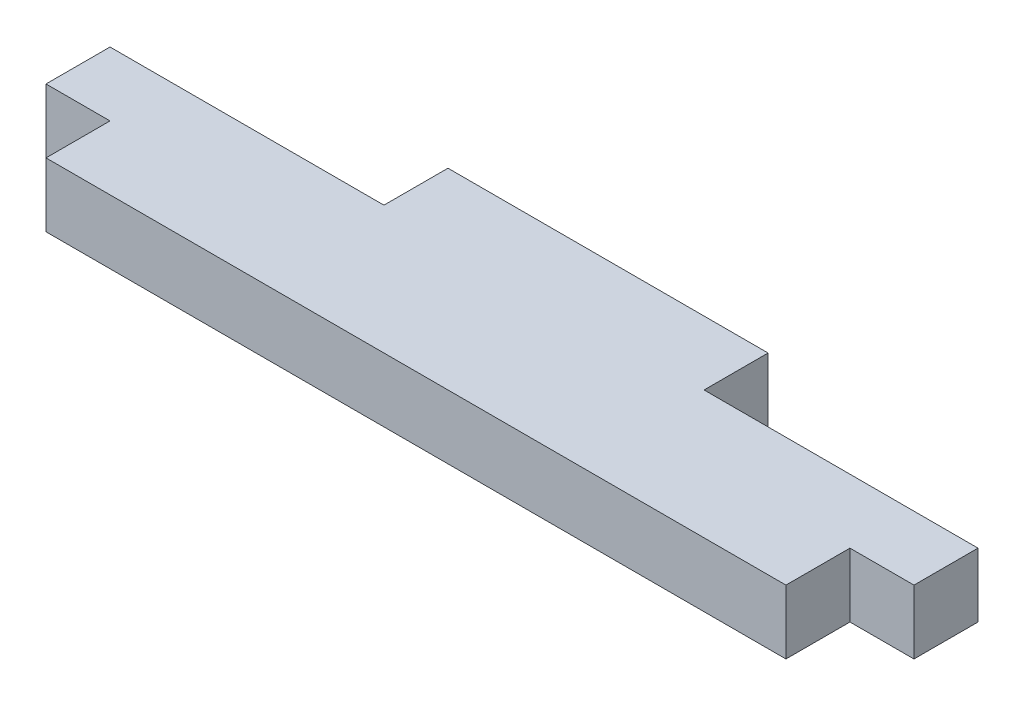
SolidWorks part; units mm, degrees
ref_plane "Front Plane" through (0, 0, 0) normal (0, 0, 1) x (1, 0, 0)
ref_plane "Top Plane" through (0, 0, 0) normal (0, 1, 0) x (1, 0, 0)
ref_plane "Right Plane" through (0, 0, 0) normal (1, 0, 0) x (0, 0, -1)
sketch "Sketch1" plane through (0, 0, 0) normal (0, 0, 1) x (1, 0, 0)
  line L1 (-33.894, -45) -> (33.894, -45)
  line L2 (-33.894, -45) -> (-33.894, -50)
  line L3 (-33.894, -50) -> (33.894, -50)
  line L4 (33.894, -45) -> (33.894, -50)
extrude "Boss-Extrude1" add sketch "Sketch1" along normal blind 5
sketch "Sketch2" plane through (0, 0, 5) normal (0, 0, 1) x (1, 0, 0)
  line L0 (33.894, -45) -> (-33.894, -45) construction
  line L1 (-28.894, -45) -> (28.894, -45)
  line L2 (-28.894, -45) -> (-28.894, -50)
  line L3 (-28.894, -50) -> (28.894, -50)
  line L4 (28.894, -45) -> (28.894, -50)
  line L5 (-28.894, -29) -> (-28.894, -53) construction
  line L6 (-33.894, -50) -> (33.894, -50) construction
  line L7 (28.894, -53) -> (28.894, -29) construction
extrude "Boss-Extrude2" add sketch "Sketch2" along normal blind 5
sketch "Sketch3" plane through (0, -50, 0) normal (0, -1, 0) x (1, 0, 0)
  line L0 (0, 10) -> (0, -25.52) construction
  line L1 (-28.894, 10) -> (28.894, 10) construction
  line L2 (-33.894, 0) -> (33.894, 0) construction
  line L3 (12.5, 0) -> (-12.5, 0)
  line L4 (12.5, 0) -> (12.5, -5)
  line L5 (12.5, -5) -> (-12.5, -5)
  line L6 (-12.5, 0) -> (-12.5, -5)
  line L7 (-16.394, -5) -> (16.394, -5) construction
  point P13 (0, 0)
  dimension "D1" = 25
extrude "Boss-Extrude3" add sketch "Sketch3" against normal blind 5
